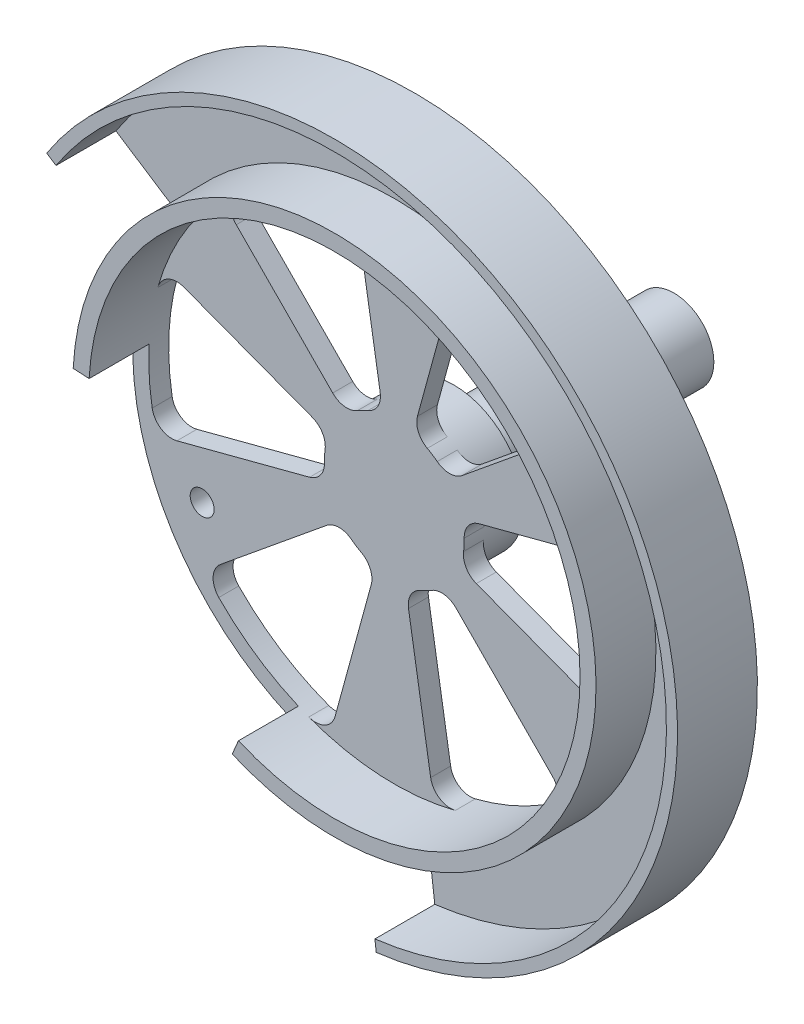
SolidWorks part; units mm, degrees
ref_plane "Piano frontale" through (0, 0, 0) normal (0, 0, 1) x (1, 0, 0)
ref_plane "Piano superiore" through (0, 0, 0) normal (0, 1, 0) x (1, 0, 0)
ref_plane "Piano destro" through (0, 0, 0) normal (1, 0, 0) x (0, 0, -1)
sketch "Schizzo1" plane through (0, 0, 0) normal (0, 0, 1) x (1, 0, 0)
  circle A0 centre (0, 0) radius 10
  dimension "D1" = 20
extrude "Estrusione-Estrusione1" add sketch "Schizzo1" along normal blind 55
sketch "Schizzo2" plane through (0, 0, 55) normal (0, 0, 1) x (1, 0, 0)
  circle A0 centre (0, 0) radius 17.5
  dimension "D1" = 35
extrude "Estrusione-Estrusione2" add sketch "Schizzo2" along normal blind 10
sketch "Schizzo3" plane through (0, 0, 65) normal (0, 0, 1) x (1, 0, 0)
  circle A0 centre (0, 0) radius 85.905
  dimension "D1" = 171.81
extrude "Estrusione-Estrusione3" add sketch "Schizzo3" along normal blind 5
sketch "Schizzo4" plane through (0, 0, 70) normal (0, 0, 1) x (1, 0, 0)
  line L0 (-72.046, 46.7872) -> (-69.7145, 45.2731)
  line L1 (10.4692, -85.2647) -> (10.1304, -82.5054)
  line L2 (0, 0) -> (0, 98.7044) construction
  circle A1 centre (0, 0) radius 83.125
  circle A2 centre (0, 0) radius 85.905
  circle M6 centre (0, 0) radius 85.905
  dimension "D1" = 166.25
  dimension "D2" = 171.81
  dimension "D3" = 57
  dimension "D4" = 130
extrude "Estrusione-Estrusione4" add sketch "Schizzo4" along normal blind 15 contours A1 L2 A2 L0 | L2 A1 L1 M6
sketch "Schizzo5" plane through (0, 0, 70) normal (0, 0, 1) x (1, 0, 0)
  line L0 (-72.046, 46.7872) -> (-54.9329, 35.6739)
  line L1 (10.4692, -85.2647) -> (7.9824, -65.0118)
  line L2 (10.1304, -82.5054) -> (10.4692, -85.2647)
  line L3 (-72.046, 46.7872) -> (-69.7145, 45.2731)
  line L4 (10.1304, -82.5054) -> (10.4692, -85.2647)
  line L5 (-72.046, 46.7872) -> (-69.7145, 45.2731)
  circle A0 centre (0, 0) radius 65.5
  arc A3 (10.1304, -82.5054) -> (-69.7145, 45.2731) centre (0, 0) ccw
  arc A4 (10.4692, -85.2647) -> (-72.046, 46.7872) centre (0, 0) ccw
  arc A5 (10.1304, -82.5054) -> (-69.7145, 45.2731) centre (0, 0) ccw
  arc A6 (10.4692, -85.2647) -> (-72.046, 46.7872) centre (0, 0) ccw
  line M6 (-69.7145, 45.2731) -> (-72.046, 46.7872)
  arc M7 (-72.046, 46.7872) -> (10.4692, -85.2647) centre (0, 0) ccw
  line M8 (10.4692, -85.2647) -> (10.1304, -82.5054)
  dimension "D1" = 131
  dimension "D2" = 0
extrude "Taglio-Estrusione1" cut sketch "Schizzo5" against normal through all contours A0 L0 L1 M6 M7 M8
sketch "Schizzo6" plane through (0, 0, 70) normal (0, 0, 1) x (1, 0, 0)
  circle A0 centre (0, 0) radius 65.5
  circle A1 centre (0, 0) radius 61.5
  dimension "D1" = 131
  dimension "D2" = 123
extrude "Estrusione-Estrusione5" add sketch "Schizzo6" along normal blind 15
sketch "Schizzo7" plane through (0, 0, 70) normal (0, 0, 1) x (1, 0, 0)
  line L0 (0, 0) -> (0, 96.1462) construction
  line L1 (-9.0948, 55.5386) -> (-3.5452, 21.6491)
  line L2 (-39.5859, 40.0026) -> (-15.4307, 15.5931)
  line L3 (43.5504, 35.6456) -> (16.9761, 13.8947)
  line L4 (14.8503, 54.2837) -> (5.7887, 21.1599)
  line L5 (52.6452, -19.893) -> (20.5212, -7.7543)
  line L6 (54.4362, 14.2811) -> (21.2194, 5.5668)
  line L7 (9.0948, -55.5386) -> (3.5452, -21.6491)
  line L8 (39.5859, -40.0026) -> (15.4307, -15.5931)
  line L9 (-43.5504, -35.6456) -> (-16.9761, -13.8947)
  line L10 (-14.8503, -54.2837) -> (-5.7887, -21.1599)
  line L11 (-52.6452, 19.893) -> (-20.5212, 7.7543)
  line L12 (-54.4362, -14.2811) -> (-21.2194, -5.5668)
  arc A0 (-6.5951, 16.2097) -> (-9.2374, 14.8634) centre (0, 0) ccw
  circle A1 centre (0, 0) radius 61.5 construction
  arc A2 (-39.2205, 47.3709) -> (-15.2706, 59.574) centre (0, 0) cw
  arc A3 (-39.5859, 40.0026) -> (-39.2205, 47.3709) centre (-36.0319, 43.5196) cw
  arc A4 (-9.0948, 55.5386) -> (-15.2706, 59.574) centre (-14.0291, 54.7306) ccw
  arc A5 (-3.5452, 21.6491) -> (-6.5951, 16.2097) centre (-8.4794, 20.841) cw
  arc A6 (-15.4307, 15.5931) -> (-9.2374, 14.8634) centre (-11.8767, 19.1101) ccw
  arc A7 (21.4141, 57.6514) -> (43.9573, 43.0117) centre (0, 0) cw
  arc A8 (43.5504, 35.6456) -> (43.9573, 43.0117) centre (40.3835, 39.5148) ccw
  arc A9 (14.8503, 54.2837) -> (21.4141, 57.6514) centre (19.6731, 52.9643) cw
  arc A10 (16.9761, 13.8947) -> (10.7404, 13.8164) centre (13.8091, 17.7639) cw
  arc A11 (10.7404, 13.8164) -> (8.2534, 15.4315) centre (0, 0) ccw
  arc A12 (5.7887, 21.1599) -> (8.2534, 15.4315) centre (10.6115, 19.8405) ccw
  arc A13 (60.6346, 10.2806) -> (59.2279, -16.5623) centre (0, 0) cw
  arc A14 (52.6452, -19.893) -> (59.2279, -16.5623) centre (54.4126, -15.2158) ccw
  arc A15 (54.4362, 14.2811) -> (60.6346, 10.2806) centre (55.705, 9.4447) cw
  arc A16 (20.5212, -7.7543) -> (17.3356, -2.3933) centre (22.2886, -3.0771) cw
  arc A17 (17.3356, -2.3933) -> (17.4908, 0.5681) centre (0, 0) ccw
  arc A18 (21.2194, 5.5668) -> (17.4908, 0.5681) centre (22.4881, 0.7305) ccw
  arc A19 (39.2205, -47.3709) -> (15.2706, -59.574) centre (0, 0) cw
  arc A20 (9.0948, -55.5386) -> (15.2706, -59.574) centre (14.0291, -54.7306) ccw
  arc A21 (39.5859, -40.0026) -> (39.2205, -47.3709) centre (36.0319, -43.5196) cw
  arc A22 (3.5452, -21.6491) -> (6.5951, -16.2097) centre (8.4794, -20.841) cw
  arc A23 (6.5951, -16.2097) -> (9.2374, -14.8634) centre (0, 0) ccw
  arc A24 (15.4307, -15.5931) -> (9.2374, -14.8634) centre (11.8767, -19.1101) ccw
  arc A25 (-21.4141, -57.6514) -> (-43.9573, -43.0117) centre (0, 0) cw
  arc A26 (-43.5504, -35.6456) -> (-43.9573, -43.0117) centre (-40.3835, -39.5148) ccw
  arc A27 (-14.8503, -54.2837) -> (-21.4141, -57.6514) centre (-19.6731, -52.9643) cw
  arc A28 (-16.9761, -13.8947) -> (-10.7404, -13.8164) centre (-13.8091, -17.7639) cw
  arc A29 (-10.7404, -13.8164) -> (-8.2534, -15.4315) centre (0, 0) ccw
  arc A30 (-5.7887, -21.1599) -> (-8.2534, -15.4315) centre (-10.6115, -19.8405) ccw
  arc A31 (-60.6346, -10.2806) -> (-59.2279, 16.5623) centre (0, 0) cw
  arc A32 (-52.6452, 19.893) -> (-59.2279, 16.5623) centre (-54.4126, 15.2158) ccw
  arc A33 (-54.4362, -14.2811) -> (-60.6346, -10.2806) centre (-55.705, -9.4447) cw
  arc A34 (-20.5212, 7.7543) -> (-17.3356, 2.3933) centre (-22.2886, 3.0771) cw
  arc A35 (-17.3356, 2.3933) -> (-17.4908, -0.5681) centre (0, 0) ccw
  arc A36 (-21.2194, -5.5668) -> (-17.4908, -0.5681) centre (-22.4881, -0.7305) ccw
  point P12 (-43.2588, 43.7142)
  point P15 (-9.9386, 60.6916)
  dimension "D1" = 35
  dimension "D4" = 5
  dimension "D2" = 9.3
  dimension "D3" = 35.4
  dimension "D5" = 6
extrude "Taglio-Estrusione2" cut sketch "Schizzo7" against normal through all
sketch "Schizzo8" plane through (0, 0, 85) normal (0, 0, 1) x (1, 0, 0)
  line L0 (-65.4102, 3.428) -> (-61.4157, 3.2187)
  line L1 (-25.5929, -60.2931) -> (-24.03, -56.611)
  line L2 (-69.7145, 45.2731) -> (-54.9329, 35.6739) construction
  line L3 (10.1304, -82.5054) -> (7.9824, -65.0118) construction
  circle A0 centre (0, 0) radius 65.5 construction
  arc A1 (-60.6346, -10.2806) -> (-43.9573, -43.0117) centre (0, 0) ccw construction
  circle A3 centre (0, 0) radius 61.5 construction
  arc A4 (-65.4102, 3.428) -> (-25.5929, -60.2931) centre (0, 0) ccw
  arc A5 (-24.03, -56.611) -> (-61.4157, 3.2187) centre (0, 0) cw
  dimension "D1" = 30
  dimension "D2" = 30
extrude "Taglio-Estrusione3" cut sketch "Schizzo8" against normal blind 15
sketch "Schizzo9" plane through (0, 0, 70) normal (0, 0, 1) x (1, 0, 0)
  line L2 (-54.4362, -14.2811) -> (-21.2194, -5.5668) construction
  circle A0 centre (0, 0) radius 54
  circle A1 centre (-48.116, -24.5122) radius 3
  point P5 (0, 0)
  point P10 (-48.0891, -24.565)
  dimension "D1" = 108
  dimension "D2" = 6
  dimension "D3" = 11.5
extrude "Taglio-Estrusione4" cut sketch "Schizzo9" against normal through all contours A1
